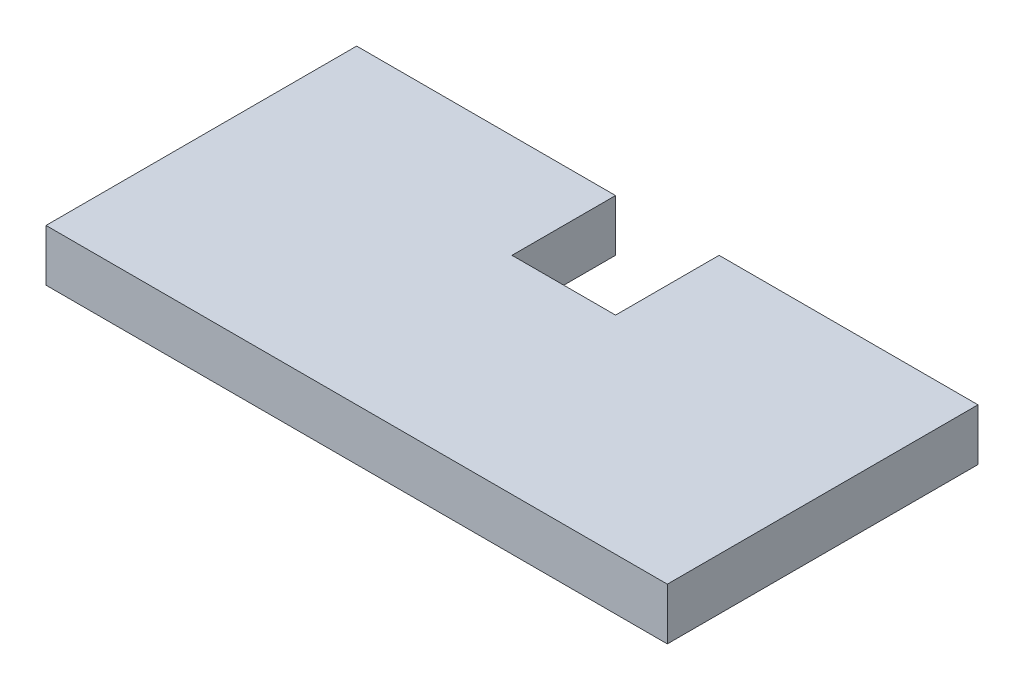
SolidWorks part; units mm, degrees
ref_plane "Front Plane" through (0, 0, 0) normal (0, 0, 1) x (1, 0, 0)
ref_plane "Top Plane" through (0, 0, 0) normal (0, 1, 0) x (1, 0, 0)
ref_plane "Right Plane" through (0, 0, 0) normal (1, 0, 0) x (0, 0, -1)
sketch "Sketch1" plane through (0, 0, 0) normal (0, 1, 0) x (1, 0, 0)
  line L1 (-516.0526, 370.5409) -> (83.9474, 370.5409)
  line L2 (-516.0526, 370.5409) -> (-516.0526, 70.5409)
  line L3 (-516.0526, 70.5409) -> (83.9474, 70.5409)
  line L4 (83.9474, 370.5409) -> (83.9474, 70.5409)
  dimension "D1" = 600
  dimension "D2" = 300
extrude "Boss-Extrude1" add sketch "Sketch1" along normal blind 50 contours L3 L4 L1 L2
sketch "Sketch2" plane through (0, 0, -370.5409) normal (0, 0, -1) x (-1, 0, 0)
  line L0 (516.0526, 50) -> (-83.9474, 50) construction
  line L1 (166.0526, 50) -> (266.0526, 50)
  line L2 (166.0526, 50) -> (166.0526, 0)
  line L3 (166.0526, 0) -> (266.0526, 0)
  line L4 (266.0526, 50) -> (266.0526, 0)
  line L5 (516.0526, 0) -> (-83.9474, 0) construction
  line L6 (-83.9474, 50) -> (-83.9474, 0) construction
  dimension "D1" = 100
  dimension "D2" = 250
  dimension "D3" = 50
extrude "Cut-Extrude1" cut sketch "Sketch2" against normal blind 100 contours L2 L3 L4 L1
equation "\"BaseWidth\"= 600"
equation "\"BaseLength\"= 300"
equation "\"D1@Sketch1\"=\"BaseWidth\""
equation "\"D2@Sketch1\"=\"BaseLength\""
equation "\"BaseHeight\"= 50"
equation "\"D1@Boss-Extrude1\"=\"BaseHeight\""
equation "\"BeamWidth\"= 100"
equation "\"D1@Sketch2\"=\"BeamWidth\""
equation "\"D2@Sketch2\"=(\"BaseWidth\"-\"BeamWidth\")/2"
equation "\"BeamLength\"= 100"
equation "\"D1@Cut-Extrude1\"=\"BeamLength\""
